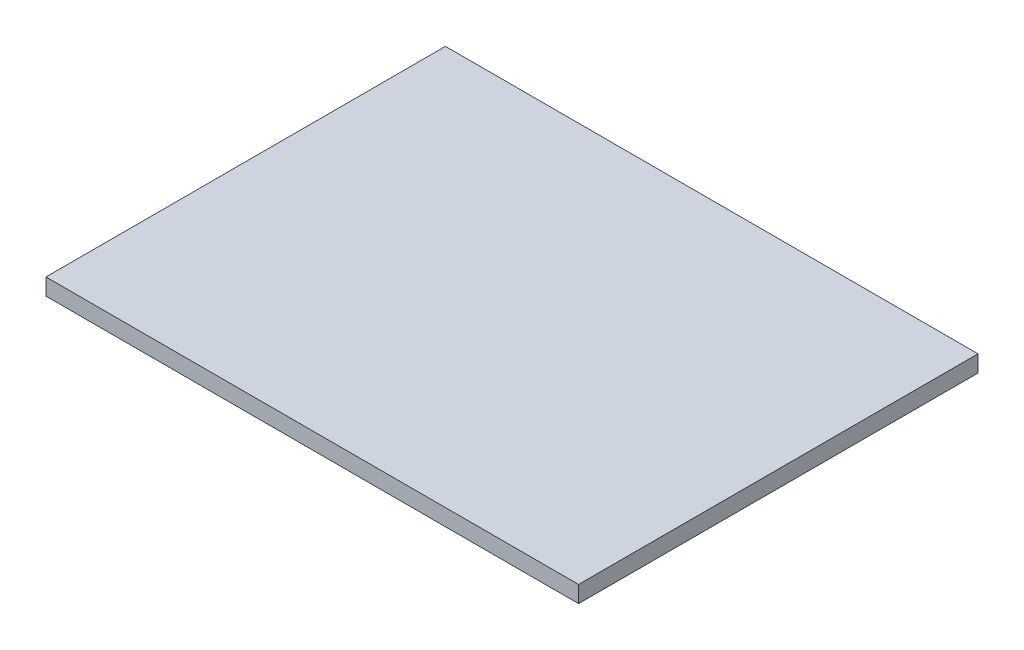
SolidWorks part; units mm, degrees
ref_plane "Front Plane" through (0, 0, 0) normal (0, 0, 1) x (1, 0, 0)
ref_plane "Top Plane" through (0, 0, 0) normal (0, 1, 0) x (1, 0, 0)
ref_plane "Right Plane" through (0, 0, 0) normal (1, 0, 0) x (0, 0, -1)
sketch "Sketch1" plane through (0, 0, 0) normal (0, 1, 0) x (1, 0, 0)
  line L1 (0, 0) -> (-32, 0)
  line L2 (0, 0) -> (0, -24)
  line L3 (0, -24) -> (-32, -24)
  line L4 (-32, 0) -> (-32, -24)
  dimension "D1" = 32
  dimension "D2" = 24
extrude "Boss-Extrude1" add sketch "Sketch1" along normal blind 1
equation "\"largo\"= 3.2"
equation "\"D1@Sketch1\"=\"largo\""
equation "\"ancho\"=2.4"
equation "\"D2@Sketch1\"=\"ancho\""
equation "\"alto\"=0.1"
equation "\"D1@Boss-Extrude1\"=\"alto\""
